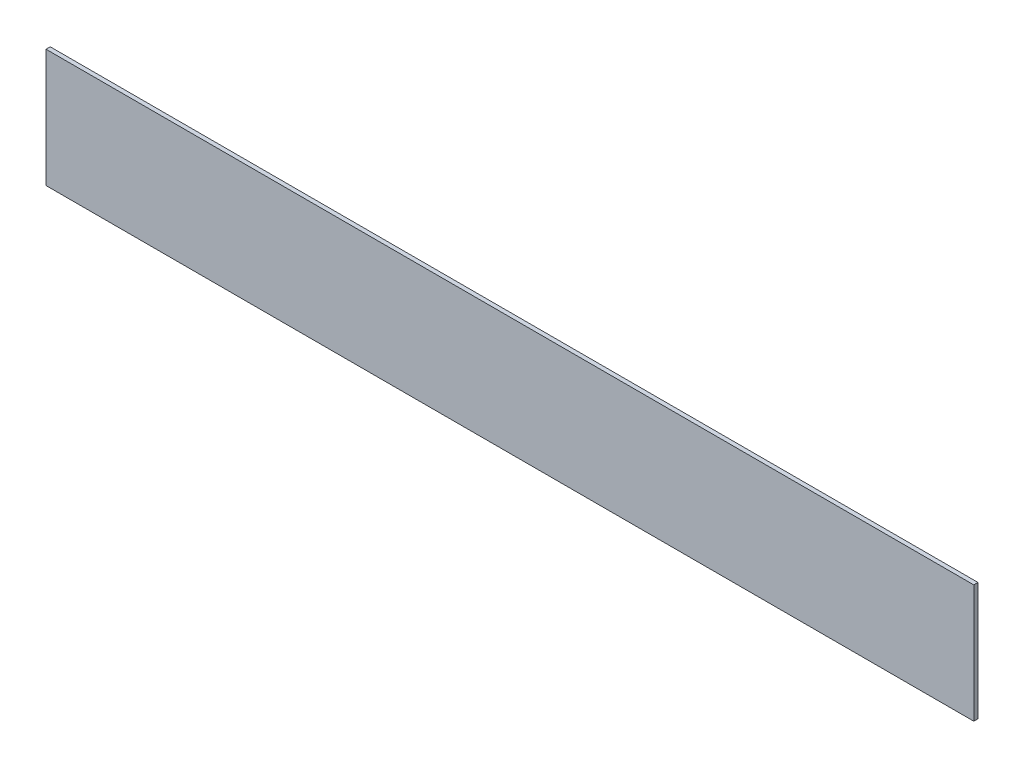
SolidWorks part; units mm, degrees
material "Delrin 2700 NC010, Low Viscosity Acetal Copolymer (SS)"
ref_plane "Front Plane" through (0, 0, 0) normal (0, 0, 1) x (1, 0, 0)
ref_plane "Top Plane" through (0, 0, 0) normal (0, 1, 0) x (1, 0, 0)
ref_plane "Right Plane" through (0, 0, 0) normal (1, 0, 0) x (0, 0, -1)
sketch "Sketch1" plane through (0, 0, 0) normal (0, 0, 1) x (1, 0, 0)
  line L1 (-349.25, -44.45) -> (349.25, -44.45)
  line L2 (-349.25, -44.45) -> (-349.25, 44.45)
  line L3 (-349.25, 44.45) -> (349.25, 44.45)
  line L4 (349.25, -44.45) -> (349.25, 44.45)
  line L5 (-349.25, -44.45) -> (349.25, 44.45) construction
  line L6 (-349.25, 44.45) -> (349.25, -44.45) construction
  point P0 (0, 0)
  dimension "D1" = 698.5
  dimension "D2" = 88.9
extrude "Boss-Extrude2" add sketch "Sketch1" along normal mid plane 3.175
